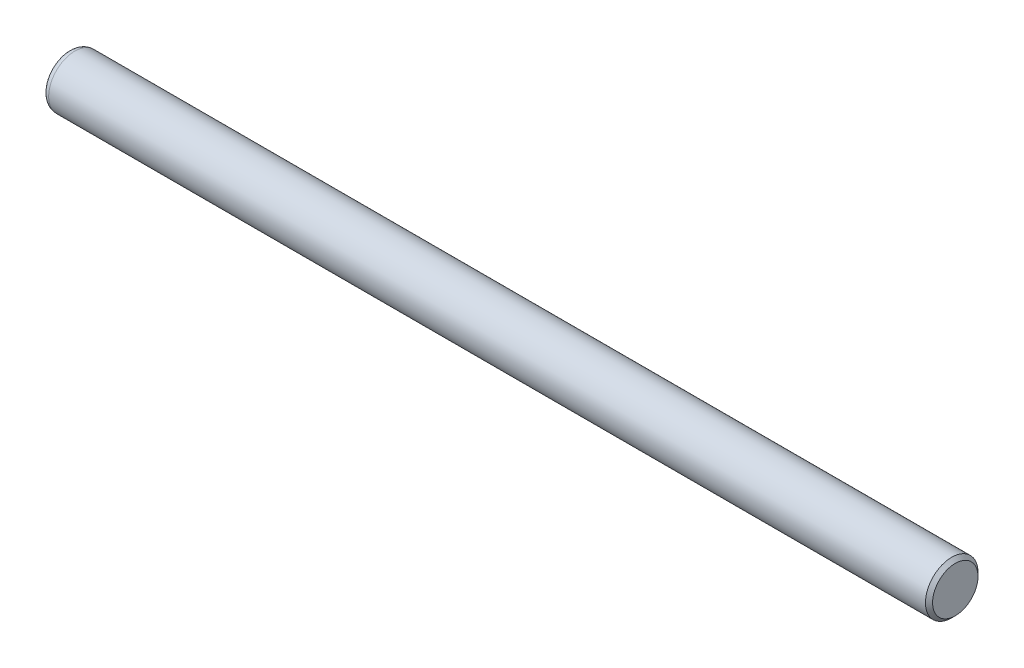
SolidWorks part; units mm, degrees
material "6061-O (SS)"
ref_plane "Ebene vorne" through (0, 0, 0) normal (0, 0, 1) x (1, 0, 0)
ref_plane "Ebene oben" through (0, 0, 0) normal (0, 1, 0) x (1, 0, 0)
ref_plane "Ebene rechts" through (0, 0, 0) normal (1, 0, 0) x (0, 0, -1)
sketch "Skizze1" plane through (0, 0, 0) normal (0, 0, 1) x (1, 0, 0)
  line L0 (0, 3.4588) -> (0, 0)
  line L1 (0, 0) -> (1000, 0)
  line L2 (1000, 0) -> (1000, 3.4588)
  line L3 (1000, 3.4588) -> (999.4588, 4)
  line L4 (999.4588, 4) -> (0.5412, 4)
  line L5 (0.5412, 4) -> (0, 3.4588)
  line L6 (0, 0) -> (1000, 0) construction
revolve "Rotation1" add sketch "Skizze1" angle 360 about L6
sketch "Skizze2" plane through (0, 0, 0) normal (0, 0, 1) x (1, 0, 0)
  line L0 (0, 3.4588) -> (0, -3.4588) construction
  line L1 (-5, 9) -> (865, 9)
  line L2 (-5, 9) -> (-5, -9)
  line L3 (-5, -9) -> (865, -9)
  line L4 (865, 9) -> (865, -9)
  line L5 (999.4588, 4) -> (0.5412, 4) construction
  line L6 (0.5412, -4) -> (999.4588, -4) construction
  line L7 (1000, -3.4588) -> (1000, 3.4588) construction
  dimension "D1" = 5
  dimension "D2" = 5
  dimension "D3" = 5
  dimension "D4" = 135
extrude "Schnitt-Linear austragen1" cut sketch "Skizze2" against normal through all both and the other way through all
fillet "Verrundung1" radius 1 1 edges at (865, 0, -4)
